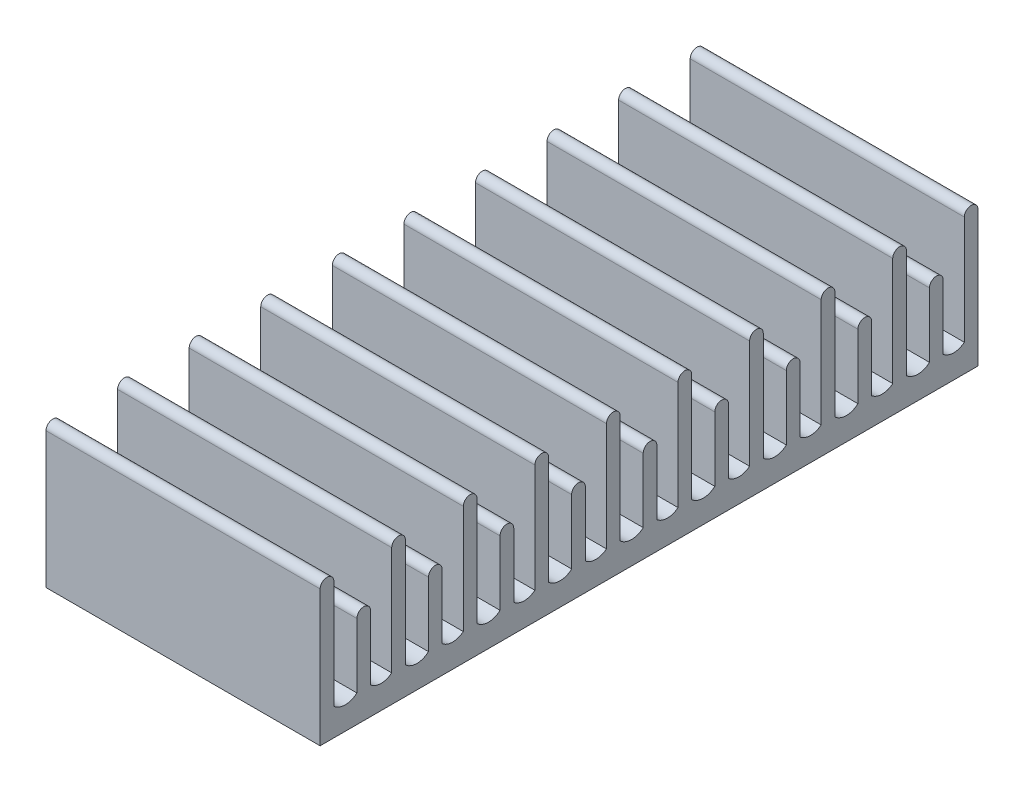
SolidWorks part; units mm, degrees
material "АД31 ГОСТ 4784-97"
ref_plane "Front Plane" through (0, 0, 0) normal (0, 0, 1) x (1, 0, 0)
ref_plane "Top Plane" through (0, 0, 0) normal (0, 1, 0) x (1, 0, 0)
ref_plane "Right Plane" through (0, 0, 0) normal (1, 0, 0) x (0, 0, -1)
sketch "Sketch1" plane through (0, 0, 0) normal (1, 0, 0) x (0, 0, -1)
  line L0 (27.9854, 81.3947) -> (139.9269, 81.3947) construction
  line L1 (-60, 6.039) -> (60, 6.039)
  line L2 (-60, 6.039) -> (-60, 30.8188)
  line L3 (-57.5007, 30.8188) -> (-57.5007, 11.039)
  line L4 (-53.2912, 11.039) -> (-53.2912, 22.789)
  line L5 (-50.7912, 22.789) -> (-50.7912, 11.039)
  line L6 (-40.2356, 11.039) -> (-40.2356, 22.789)
  line L7 (-44.4451, 30.8188) -> (-44.4451, 11.039)
  line L8 (-37.7356, 22.789) -> (-37.7356, 11.039)
  line L9 (-27.1799, 11.039) -> (-27.1799, 22.789)
  line L10 (-31.3894, 30.8188) -> (-31.3894, 11.039)
  line L11 (-24.6799, 22.789) -> (-24.6799, 11.039)
  line L12 (-14.1243, 11.039) -> (-14.1243, 22.789)
  line L13 (-18.3338, 30.8188) -> (-18.3338, 11.039)
  line L14 (-11.6243, 22.789) -> (-11.6243, 11.039)
  line L15 (-1.0687, 11.039) -> (-1.0687, 22.789)
  line L16 (-5.2782, 30.8188) -> (-5.2782, 11.039)
  line L17 (1.4313, 22.789) -> (1.4313, 11.039)
  line L18 (11.987, 11.039) -> (11.987, 22.789)
  line L19 (7.7775, 30.8188) -> (7.7775, 11.039)
  line L20 (14.487, 22.789) -> (14.487, 11.039)
  line L21 (25.0426, 11.039) -> (25.0426, 22.789)
  line L22 (20.8331, 30.8188) -> (20.8331, 11.039)
  line L23 (27.5426, 22.789) -> (27.5426, 11.039)
  line L24 (38.0982, 11.039) -> (38.0982, 22.789)
  line L25 (33.8887, 30.8188) -> (33.8887, 11.039)
  line L26 (40.5982, 22.789) -> (40.5982, 11.039)
  line L27 (51.1539, 11.039) -> (51.1539, 22.789)
  line L28 (46.9444, 30.8188) -> (46.9444, 11.039)
  line L29 (53.6539, 22.789) -> (53.6539, 11.039)
  line L30 (-46.9444, 11.039) -> (-46.9444, 30.8188)
  line L31 (60, 30.8188) -> (60, 6.039)
  line L32 (-58.7504, 30.789) -> (58.7504, 30.789) construction
  line L33 (64.2095, 11.039) -> (64.2095, 22.789) [skipped]
  line L34 (66.7095, 22.789) -> (66.7095, 11.039) [skipped]
  line L35 (58.7504, 32.039) -> (61.6936, 32.039) construction
  line L36 (-57.5007, 11.039) -> (57.1332, 11.039) construction
  line L37 (-33.8887, 11.039) -> (-33.8887, 30.8188)
  line L38 (-20.8331, 11.039) -> (-20.8331, 30.8188)
  line L39 (-7.7775, 11.039) -> (-7.7775, 30.8188)
  line L40 (5.2782, 11.039) -> (5.2782, 30.8188)
  line L41 (18.3338, 11.039) -> (18.3338, 30.8188)
  line L42 (31.3894, 11.039) -> (31.3894, 30.8188)
  line L43 (44.4451, 11.039) -> (44.4451, 30.8188)
  line L44 (57.5007, 11.039) -> (57.5007, 30.8188)
  line L45 (-58.7504, 32.039) -> (-65.8372, 32.039) construction
  line L46 (0, 0) -> (0, 49.2233) construction
  arc A0 (-60, 30.8188) -> (-57.5007, 30.8188) centre (-58.7504, 30.789) cw
  arc A1 (-57.5007, 11.039) -> (-53.2912, 11.039) centre (-55.396, 13.3304) ccw
  arc A2 (-53.2912, 22.789) -> (-50.7912, 22.789) centre (-52.0412, 22.789) cw
  arc A3 (-44.4451, 11.039) -> (-40.2356, 11.039) centre (-42.3403, 13.3304) ccw
  arc A4 (-46.9444, 30.8188) -> (-44.4451, 30.8188) centre (-45.6947, 30.789) cw
  arc A5 (-40.2356, 22.789) -> (-37.7356, 22.789) centre (-38.9856, 22.789) cw
  arc A6 (-31.3894, 11.039) -> (-27.1799, 11.039) centre (-29.2847, 13.3304) ccw
  arc A7 (-33.8887, 30.8188) -> (-31.3894, 30.8188) centre (-32.6391, 30.789) cw
  arc A8 (-27.1799, 22.789) -> (-24.6799, 22.789) centre (-25.9299, 22.789) cw
  arc A9 (-18.3338, 11.039) -> (-14.1243, 11.039) centre (-16.2291, 13.3304) ccw
  arc A10 (-20.8331, 30.8188) -> (-18.3338, 30.8188) centre (-19.5835, 30.789) cw
  arc A11 (-14.1243, 22.789) -> (-11.6243, 22.789) centre (-12.8743, 22.789) cw
  arc A12 (-5.2782, 11.039) -> (-1.0687, 11.039) centre (-3.1734, 13.3304) ccw
  arc A13 (-7.7775, 30.8188) -> (-5.2782, 30.8188) centre (-6.5278, 30.789) cw
  arc A14 (-1.0687, 22.789) -> (1.4313, 22.789) centre (0.1813, 22.789) cw
  arc A15 (7.7775, 11.039) -> (11.987, 11.039) centre (9.8822, 13.3304) ccw
  arc A16 (5.2782, 30.8188) -> (7.7775, 30.8188) centre (6.5278, 30.789) cw
  arc A17 (11.987, 22.789) -> (14.487, 22.789) centre (13.237, 22.789) cw
  arc A18 (20.8331, 11.039) -> (25.0426, 11.039) centre (22.9379, 13.3304) ccw
  arc A19 (18.3338, 30.8188) -> (20.8331, 30.8188) centre (19.5835, 30.789) cw
  arc A20 (25.0426, 22.789) -> (27.5426, 22.789) centre (26.2926, 22.789) cw
  arc A21 (33.8887, 11.039) -> (38.0982, 11.039) centre (35.9935, 13.3304) ccw
  arc A22 (31.3894, 30.8188) -> (33.8887, 30.8188) centre (32.6391, 30.789) cw
  arc A23 (38.0982, 22.789) -> (40.5982, 22.789) centre (39.3482, 22.789) cw
  arc A24 (46.9444, 11.039) -> (51.1539, 11.039) centre (49.0491, 13.3304) ccw
  arc A25 (44.4451, 30.8188) -> (46.9444, 30.8188) centre (45.6947, 30.789) cw
  arc A26 (51.1539, 22.789) -> (53.6539, 22.789) centre (52.4039, 22.789) cw
  arc A27 (-50.7912, 11.039) -> (-46.9444, 11.039) centre (-48.8678, 13.3304) ccw
  arc A28 (57.5007, 30.8188) -> (60, 30.8188) centre (58.7504, 30.789) cw
  arc A29 (-37.7356, 11.039) -> (-33.8887, 11.039) centre (-35.8121, 13.3304) ccw
  arc A30 (60, 11.039) -> (64.2095, 11.039) centre (62.1048, 13.3304) ccw [skipped]
  arc A31 (64.2095, 22.789) -> (66.7095, 22.789) centre (65.4595, 22.789) cw [skipped]
  arc A32 (-24.6799, 11.039) -> (-20.8331, 11.039) centre (-22.7565, 13.3304) ccw
  arc A33 (-11.6243, 11.039) -> (-7.7775, 11.039) centre (-9.7009, 13.3304) ccw
  arc A34 (1.4313, 11.039) -> (5.2782, 11.039) centre (3.3548, 13.3304) ccw
  arc A35 (14.487, 11.039) -> (18.3338, 11.039) centre (16.4104, 13.3304) ccw
  arc A36 (27.5426, 11.039) -> (31.3894, 11.039) centre (29.466, 13.3304) ccw
  arc A37 (40.5982, 11.039) -> (44.4451, 11.039) centre (42.5217, 13.3304) ccw
  arc A38 (53.6539, 11.039) -> (57.5007, 11.039) centre (55.5773, 13.3304) ccw
  point P103 (0, 6.039)
  point P104 (0, 0)
  point P117 (0, 0)
  point P120 (0, 0)
  point P123 (0, 0)
  point P124 (0, 0)
  point P127 (0, 0)
  point P128 (0, 0)
  point P131 (0, 0)
  dimension "D2" = 13.0556
  dimension "D3" = 2.4993
  dimension "D4" = 10
  dimension "D1" = 120
  dimension "D5" = 26
  dimension "D6" = 9
  dimension "D7" = 21
  dimension "D8" = 8
  dimension "D9" = 2.5
extrude "Boss-Extrude1" add sketch "Sketch1" along normal mid plane 50
